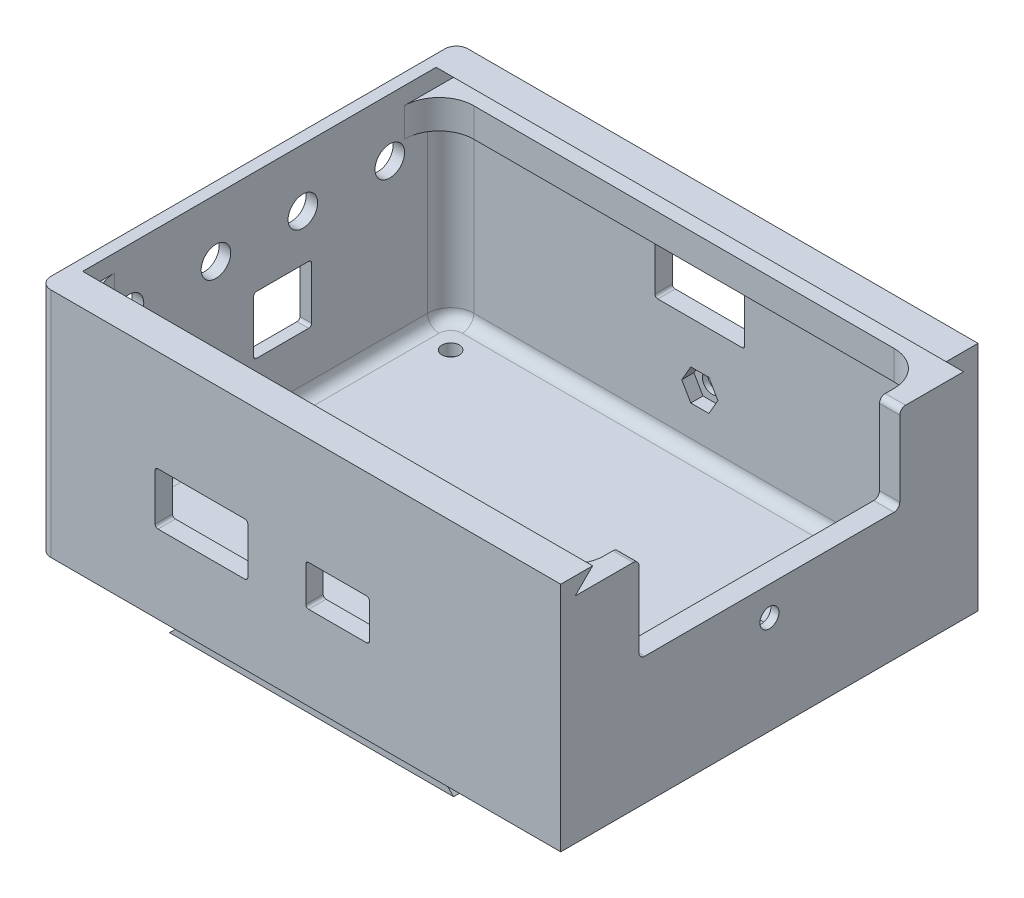
SolidWorks part; units mm, degrees
ref_plane "Front Plane" through (0, 0, 0) normal (0, 0, 1) x (1, 0, 0)
ref_plane "Top Plane" through (0, 0, 0) normal (0, 1, 0) x (1, 0, 0)
ref_plane "Right Plane" through (0, 0, 0) normal (1, 0, 0) x (0, 0, -1)
sketch "Sketch1" plane through (0, 0, 0) normal (0, 1, 0) x (1, 0, 0)
  line L1 (45, -36) -> (-45, -36)
  line L2 (45, -36) -> (45, 36)
  line L3 (45, 36) -> (-45, 36)
  line L4 (-45, -36) -> (-45, 36)
  line L5 (45, -36) -> (-45, 36) construction
  line L6 (45, 36) -> (-45, -36) construction
  point P0 (0, 0)
  dimension "D1" = 90
  dimension "D2" = 72
extrude "Boss-Extrude1" add sketch "Sketch1" along normal blind 40
shell "Shell1" thickness 2
sketch "Sketch2" plane through (0, 2, 0) normal (0, 1, 0) x (1, 0, 0)
  line L1 (40, -30) -> (-40, -30) construction
  line L2 (40, -30) -> (40, 30) construction
  line L3 (40, 30) -> (-40, 30) construction
  line L4 (-40, -30) -> (-40, 30) construction
  line L5 (40, -30) -> (-40, 30) construction
  line L6 (40, 30) -> (-40, -30) construction
  circle A0 centre (37.5, 27.5) radius 1.5
  circle A1 centre (-37.5, 27.5) radius 1.5
  circle A2 centre (-37.5, -27.5) radius 1.5
  circle A3 centre (37.5, -27.5) radius 1.5
  point P0 (0, 0)
  dimension "D4" = 3
  dimension "D6" = 55
  dimension "D1" = 80
  dimension "D2" = 60
  dimension "D3" = 2.5
  dimension "D5" = 2.5
  dimension "D7" = 2.5
extrude "Cut-Extrude1" cut sketch "Sketch2" against normal up to surface (2 mm away) up to face at (0, 0, 0)
sketch "Sketch3" plane through (45, 0, 0) normal (1, 0, 0) x (0, 0, -1)
  line L0 (-30.5, 40) -> (-33.5, 37)
  line L1 (-36, 40) -> (36, 40) construction
  line L2 (-33.5, 37) -> (33.5, 37)
  line L3 (33.5, 37) -> (30.5, 40)
  line L4 (30.5, 40) -> (-30.5, 40)
  line L5 (-36, 40) -> (-36, 0) construction
  line L6 (36, 40) -> (36, 0) construction
  dimension "D1" = 45
  dimension "D2" = 45
  dimension "D3" = 2.5
  dimension "D4" = 2.5
  dimension "D5" = 3
extrude "Cut-Extrude2" cut sketch "Sketch3" against normal up to surface (88 mm away) up to face at (-43, 21, 0)
sketch "Sketch4" plane through (41.5, 0, 0) normal (-1, 0, 0) x (0, 0, 1)
  line L0 (30.5, 40) -> (33, 37.5) construction
  line L1 (33, 37.5) -> (33, 40) construction
  line L2 (33, 40) -> (30.5, 40) construction
  line L3 (-33, 37.5) -> (-30.5, 40) construction
  line L4 (-30.5, 40) -> (-33, 40) construction
  line L5 (-33, 40) -> (-33, 37.5) construction
  line L6 (30.5, 40) -> (33, 37.5)
  line L7 (33, 37.5) -> (33, 40)
  line L8 (33, 40) -> (30.5, 40)
  line L9 (-33, 37.5) -> (-30.5, 40)
  line L10 (-30.5, 40) -> (-33, 40)
  line L11 (-33, 40) -> (-33, 37.5)
  line L13 (-33, 37) -> (-31, 37)
  line L14 (-33, 37) -> (-33, 32)
  line L15 (-33, 32) -> (-31, 32)
  line L16 (-31, 37) -> (-31, 32)
  line L17 (-33, 37) -> (-31, 32) construction
  line L18 (-33, 32) -> (-31, 37) construction
  line L19 (33, 37) -> (31, 37)
  line L20 (33, 37) -> (33, 32)
  line L21 (33, 32) -> (31, 32)
  line L22 (31, 37) -> (31, 32)
  line L23 (33, 37) -> (31, 32) construction
  line L24 (33, 32) -> (31, 37) construction
  point P10 (-32, 34.5)
  point P16 (32, 34.5)
  dimension "D1" = 5
  dimension "D2" = 2
  dimension "D3" = 5
  dimension "D4" = 2
extrude "Boss-Extrude2" add sketch "Sketch4" along normal up to surface (84.5 mm away)
sketch "Sketch5" plane through (45, 0, 0) normal (1, 0, 0) x (0, 0, -1)
  line L0 (-33.5, 37) -> (33.5, 37) construction
  line L1 (-22.5, 37) -> (22.5, 37)
  line L2 (-22.5, 37) -> (-22.5, 22)
  line L3 (-22.5, 22) -> (22.5, 22)
  line L4 (22.5, 37) -> (22.5, 22)
  line L5 (-22.5, 37) -> (22.5, 22) construction
  line L6 (-22.5, 22) -> (22.5, 37) construction
  circle A0 centre (0, 17) radius 1.65
  point P0 (0, 29.5)
  dimension "D3" = 3.3
  dimension "D1" = 45
  dimension "D2" = 15
  dimension "D4" = 5
extrude "Cut-Extrude3" cut sketch "Sketch5" against normal up to surface (3.5 mm away) up to face at (41.5, 25.75, 0)
sketch "Sketch6" plane through (41.5, 0, 0) normal (-1, 0, 0) x (0, 0, 1)
  line L0 (22.5, 22) -> (-22.5, 22) construction
  line L1 (3.1177, 17) -> (1.5588, 19.7)
  line L2 (1.5588, 19.7) -> (-1.5588, 19.7)
  line L3 (-1.5588, 19.7) -> (-3.1177, 17)
  line L4 (-3.1177, 17) -> (-1.5588, 14.3)
  line L5 (-1.5588, 14.3) -> (1.5588, 14.3)
  line L6 (1.5588, 14.3) -> (3.1177, 17)
  circle A0 centre (0, 17) radius 2.7 construction
  dimension "D1" = 5.4
extrude "Cut-Extrude4" cut sketch "Sketch6" against normal blind 2.1
sketch "Sketch7" plane through (-45, 0, 0) normal (-1, 0, 0) x (0, 0, 1)
  line L0 (-36, 0) -> (36, 0) construction
  line L1 (-36, 40) -> (-36, 0) construction
  line L2 (36, 40) -> (36, 0) construction
  line L4 (-9, 22) -> (1, 22)
  line L5 (-9, 22) -> (-9, 12)
  line L6 (-9, 12) -> (1, 12)
  line L7 (1, 22) -> (1, 12)
  line L8 (-9, 22) -> (1, 12) construction
  line L9 (-9, 12) -> (1, 22) construction
  circle A0 centre (-22.5, 30) radius 2.55
  circle A2 centre (-7.5, 30) radius 2.55
  circle A3 centre (7.5, 30) radius 2.55
  circle A4 centre (22.5, 30) radius 2.55
  point P14 (-4, 17)
  dimension "D2" = 5.1
  dimension "D1" = 30
  dimension "D3" = 13.5
  dimension "D5" = 13.5
  dimension "D6" = 10
  dimension "D7" = 10
  dimension "D8" = 27
  dimension "D9" = 12
  dimension "D4" = 4
extrude "Cut-Extrude5" cut sketch "Sketch7" against normal up to surface (2 mm away)
sketch "Sketch8" plane through (0, 0, 36) normal (0, 0, 1) x (1, 0, 0)
  line L0 (-45, 0) -> (45, 0) construction
  line L1 (-25, 22.5) -> (-9, 22.5)
  line L2 (-25, 22.5) -> (-25, 13.5)
  line L3 (-25, 13.5) -> (-9, 13.5)
  line L4 (-9, 22.5) -> (-9, 13.5)
  line L5 (-25, 22.5) -> (-9, 13.5) construction
  line L6 (-25, 13.5) -> (-9, 22.5) construction
  line L7 (1, 21.5) -> (12, 21.5)
  line L8 (1, 21.5) -> (1, 14.5)
  line L9 (1, 14.5) -> (12, 14.5)
  line L10 (12, 21.5) -> (12, 14.5)
  line L11 (1, 21.5) -> (12, 14.5) construction
  line L12 (1, 14.5) -> (12, 21.5) construction
  line L13 (-45, 40) -> (-45, 0) construction
  point P0 (-17, 18)
  point P5 (6.5, 18)
  dimension "D1" = 16
  dimension "D2" = 9
  dimension "D3" = 11
  dimension "D4" = 7
  dimension "D5" = 18
  dimension "D6" = 20
  dimension "D7" = 10
extrude "Cut-Extrude6" cut sketch "Sketch8" against normal up to surface (3 mm away) up to face at (-0.75, 17, 33)
sketch "Sketch9" plane through (0, 0, -36) normal (0, 0, 1) x (1, 0, 0)
  line L0 (-21.6, 0.2) -> (-25, -3.2) construction
  line L1 (-25, -3.2) -> (25, -3.2) construction
  line L2 (25, -3.2) -> (21.6, 0.2) construction
  line L3 (21.6, 0.2) -> (-21.6, 0.2) construction
  line L5 (21.5172, 0) -> (-21.5172, 0)
  line L6 (-21.5172, 0) -> (-24.5172, -3)
  line L7 (-24.5172, -3) -> (24.5172, -3)
  line L8 (24.5172, -3) -> (21.5172, 0)
  line L9 (-45, 0) -> (45, 0) construction
  point P7 (0, -3.2)
  dimension "D1" = 45
  dimension "D2" = 3
  dimension "D3" = 50
  dimension "D4" = 0.2
extrude "Boss-Extrude3" add sketch "Sketch9" along normal offset from surface (70 mm away) 2 up to face at (-17, 18, 36)
sketch "Sketch10" plane through (0, 0, -36) normal (0, 0, -1) x (-1, 0, 0)
  line L1 (-24.5172, -3) -> (24.5172, -3) construction
  line L2 (24.5172, -3) -> (-24.5172, -3) construction
  line L3 (-7.75, 31.5) -> (7.75, 31.5)
  line L4 (-7.75, 31.5) -> (-7.75, 22)
  line L5 (-7.75, 22) -> (7.75, 22)
  line L6 (7.75, 31.5) -> (7.75, 22)
  line L7 (-7.75, 31.5) -> (7.75, 22) construction
  line L8 (-7.75, 22) -> (7.75, 31.5) construction
  circle A0 centre (0, 12) radius 1.65
  point P6 (0, 26.75)
  dimension "D1" = 3.3
  dimension "D2" = 15
  dimension "D3" = 25
  dimension "D4" = 15.5
  dimension "D5" = 9.5
extrude "Cut-Extrude7" cut sketch "Sketch10" against normal up to surface (3 mm away) up to face at (-0.75, 17, -33)
sketch "Sketch11" plane through (0, 0, -33) normal (0, 0, 1) x (1, 0, 0)
  line L0 (41.5, 2) -> (-43, 2) construction
  line L1 (1.5588, 14.7) -> (-1.5588, 14.7)
  line L2 (-1.5588, 14.7) -> (-3.1177, 12)
  line L3 (-3.1177, 12) -> (-1.5588, 9.3)
  line L4 (-1.5588, 9.3) -> (1.5588, 9.3)
  line L5 (1.5588, 9.3) -> (3.1177, 12)
  line L6 (3.1177, 12) -> (1.5588, 14.7)
  circle A0 centre (0, 12) radius 2.7 construction
  dimension "D1" = 5.4
extrude "Cut-Extrude8" cut sketch "Sketch11" against normal blind 2.1
fillet "Fillet3" radius 1 4 edges at (43.25, 22, -22.5) (43.25, 37, -22.5) (43.25, 37, 22.5) (43.25, 22, 22.5)
fillet "Fillet4" radius 0.5 4 edges at (-44, 12, 1) (-44, 12, -9) (-44, 22, 1) (-44, 22, -9)
fillet "Fillet5" radius 0.5 8 edges at (12, 21.5, 34.5) (1, 21.5, 34.5) (12, 14.5, 34.5) (1, 14.5, 34.5) (-25, 13.5, 34.5) (-25, 22.5, 34.5) (-9, 22.5, 34.5) (-9, 13.5, 34.5)
fillet "Fillet6" radius 0.5 4 edges at (7.75, 22, -34.5) (-7.75, 22, -34.5) (-7.75, 31.5, -34.5) (7.75, 31.5, -34.5)
fillet "Fillet7" radius 6 4 edges at (-43, 34.5, -31) (41.5, 34.5, -31) (-43, 34.5, 31) (41.5, 34.5, 31)
fillet "Fillet8" radius 4 4 edges at (41.5, 17, -33) (-43, 17, -33) (41.5, 17, 33) (-43, 17, 33)
fillet "Fillet9" radius 2 8 edges at (40.3284, 2, 31.8284) (-41.8284, 2, 31.8284) (-41.8284, 2, -31.8284) (40.3284, 2, -31.8284) (-0.75, 2, 33) (-43, 2, 0) (-0.75, 2, -33) (41.5, 2, 0)
fillet "Fillet10" radius 2 2 edges at (-45, 20, -36) (-45, 20, 36)
